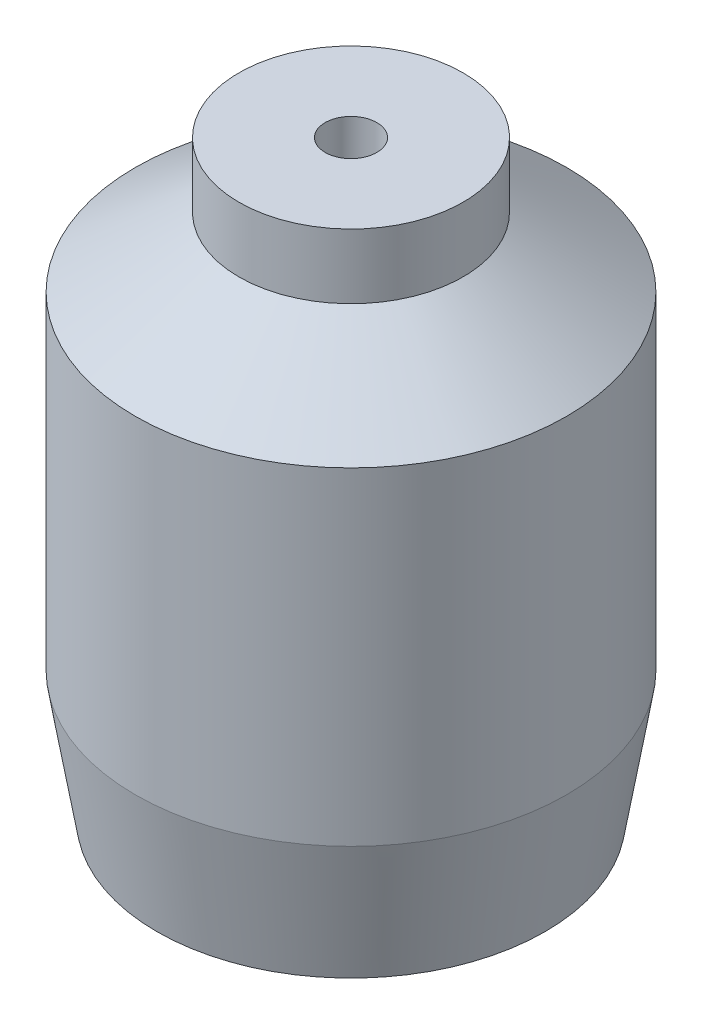
SolidWorks part; units mm, degrees
ref_plane "Front Plane" through (0, 0, 0) normal (0, 0, 1) x (1, 0, 0)
ref_plane "Top Plane" through (0, 0, 0) normal (0, 1, 0) x (1, 0, 0)
ref_plane "Right Plane" through (0, 0, 0) normal (1, 0, 0) x (0, 0, -1)
sketch "Sketch1" plane through (0, 0, 0) normal (0, 0, 1) x (1, 0, 0)
  line L0 (22.5, 0) -> (0, 0)
  line L1 (0, 0) -> (0, 15) construction
  line L2 (0, 15) -> (25, 15) construction
  line L3 (0, 15) -> (0, 53) construction
  line L4 (0, 53) -> (25, 53) construction
  line L5 (0, 53) -> (0, 61) construction
  line L6 (0, 61) -> (13, 61) construction
  line L7 (0, 61) -> (0, 68.5) construction
  line L8 (0, 68.5) -> (13, 68.5)
  line L9 (13, 68.5) -> (13, 61)
  line L10 (13, 61) -> (25, 53)
  line L11 (25, 53) -> (25, 15)
  line L12 (25, 15) -> (22.5, 0)
  line L13 (0, -22.2804) -> (0, 88.9006) construction
  line L14 (0, 0) -> (0, 68.5)
  dimension "D1" = 15
  dimension "D2" = 38
  dimension "D3" = 8
  dimension "D4" = 7.5
revolve "Revolve1" add sketch "Sketch1" angle 360 about L14
sketch "Sketch2" plane through (0, 68.5, 0) normal (0, 1, 0) x (1, 0, 0)
  circle A0 centre (0, 0) radius 3
extrude "Cut-Extrude1" cut sketch "Sketch2" against normal blind 70
